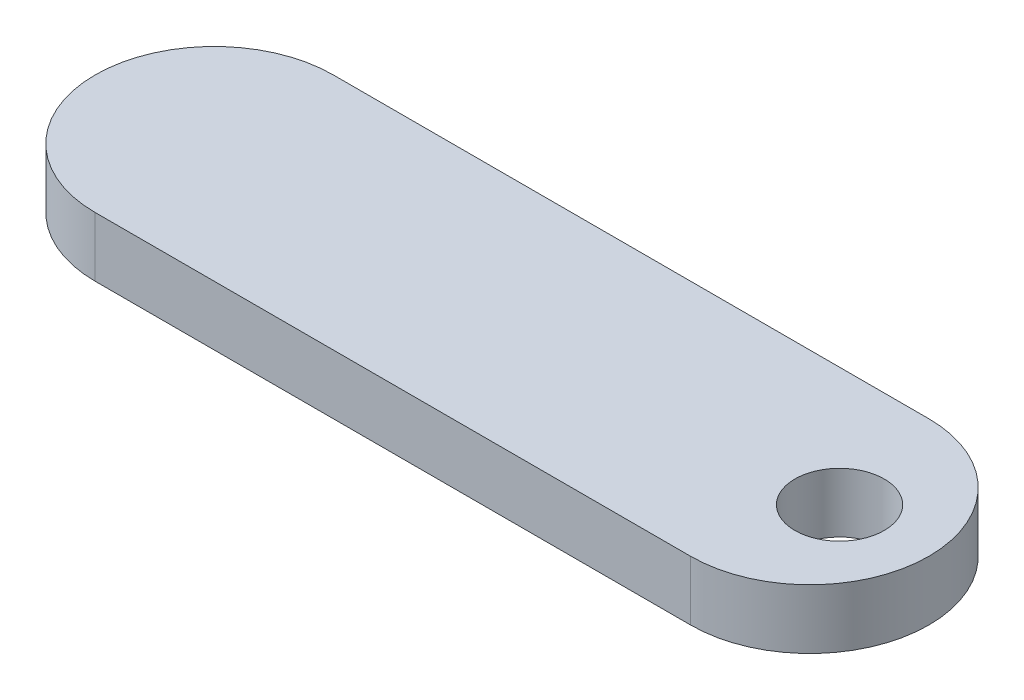
SolidWorks part; units mm, degrees
ref_plane "Front Plane" through (0, 0, 0) normal (0, 0, 1) x (1, 0, 0)
ref_plane "Top Plane" through (0, 0, 0) normal (0, 1, 0) x (1, 0, 0)
ref_plane "Right Plane" through (0, 0, 0) normal (1, 0, 0) x (0, 0, -1)
sketch "Sketch1" plane through (0, 0, 0) normal (0, 1, 0) x (1, 0, 0)
  line L0 (-12.7, 0) -> (12.7, 0) construction
  line L1 (-12.7, 5.08) -> (12.7, 5.08)
  line L2 (-12.7, -5.08) -> (12.7, -5.08)
  arc A0 (-12.7, 5.08) -> (-12.7, -5.08) centre (-12.7, 0) ccw
  arc A1 (12.7, -5.08) -> (12.7, 5.08) centre (12.7, 0) ccw
  point P2 (0, 0)
  dimension "D1" = 25.4
extrude "baton" add sketch "Sketch1" along normal blind 2.54
sketch "Sketch5" plane through (0, 2.54, 0) normal (0, 1, 0) x (1, 0, 0)
  circle A0 centre (13.97, 0) radius 1.905
  dimension "D1" = 3.81
  dimension "D2" = 13.97
extrude "joiner hole" cut sketch "Sketch5" against normal blind 2.54
